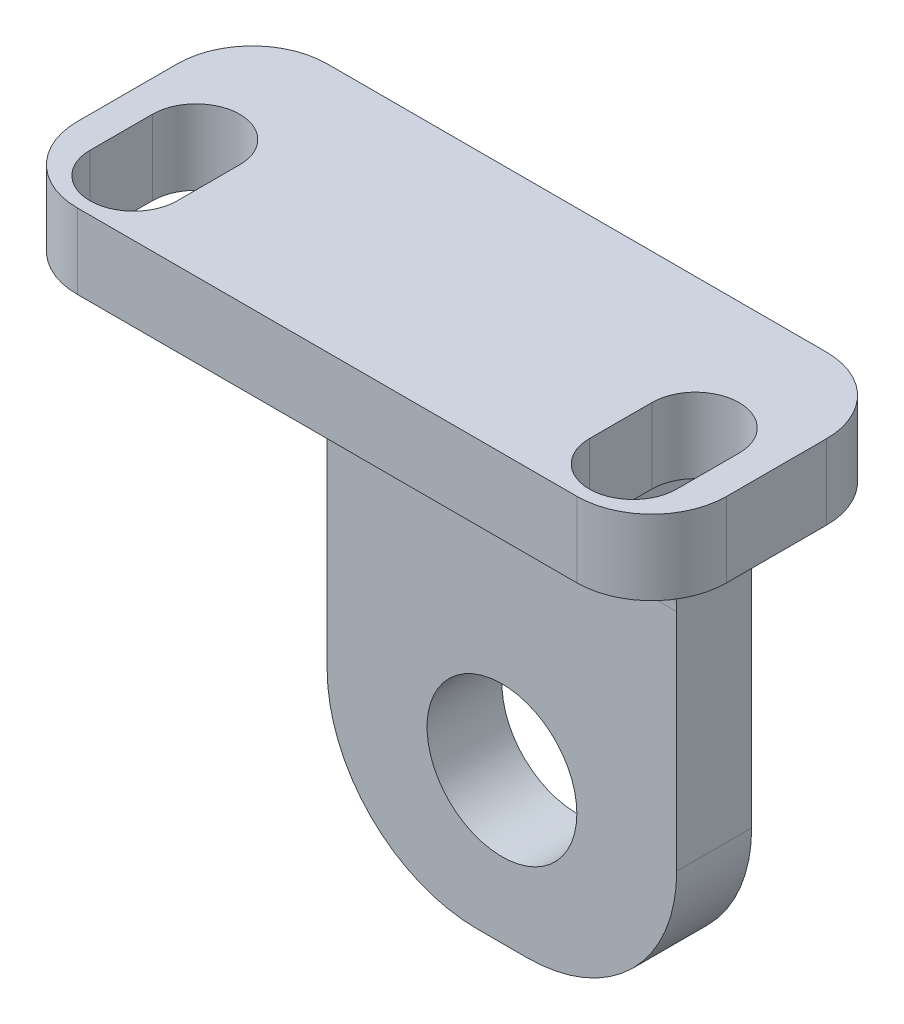
SolidWorks part; units mm, degrees
ref_plane "Front Plane" through (0, 0, 0) normal (0, 0, 1) x (1, 0, 0)
ref_plane "Top Plane" through (0, 0, 0) normal (0, 1, 0) x (1, 0, 0)
ref_plane "Right Plane" through (0, 0, 0) normal (1, 0, 0) x (0, 0, -1)
sketch "Sketch1" plane through (0, 0, 0) normal (0, 1, 0) x (1, 0, 0)
  line L1 (-7, 0) -> (7, 0)
  line L2 (-7, 0) -> (-7, -3)
  line L3 (-7, -3) -> (7, -3)
  line L4 (7, 0) -> (7, -3)
  line L5 (-7, 0) -> (7, -3) construction
  line L6 (-7, -3) -> (7, 0) construction
  point P0 (0, -1.5)
  dimension "D1" = 3
  dimension "D2" = 14
extrude "Boss-Extrude1" add sketch "Sketch1" along normal blind 24
sketch "Sketch2" plane through (0, 0, 3) normal (0, 0, 1) x (1, 0, 0)
  line L1 (-7, 0) -> (7, 0) construction
  circle A0 centre (0, 6) radius 3
  dimension "D1" = 6
  dimension "D2" = 6
extrude "Cut-Extrude1" cut sketch "Sketch2" against normal up to next
sketch "Sketch3" plane through (0, 0, 0) normal (0, 0, 1) x (1, 0, 0)
  line L1 (13, 21) -> (-13, 21)
  line L2 (13, 21) -> (13, 24)
  line L3 (13, 24) -> (-13, 24)
  line L4 (-13, 21) -> (-13, 24)
  line L5 (-7, 24) -> (7, 24) construction
  line L6 (-7, 24) -> (-7, 0) construction
  line L7 (7, 24) -> (7, 0) construction
  dimension "D1" = 6
  dimension "D2" = 6
  dimension "D3" = 3
extrude "Boss-Extrude2" add sketch "Sketch3" along normal blind 10
sketch "Sketch4" plane through (0, 24, 0) normal (0, 1, 0) x (1, 0, 0)
  line L0 (-10, -7.75) -> (-10, -5.25) construction
  line L1 (-11.75, -7.75) -> (-11.75, -5.25)
  line L2 (-8.25, -7.75) -> (-8.25, -5.25)
  line L3 (0, -5.5) -> (0, 5.5) construction
  line L4 (10, -7.75) -> (10, -5.25) construction
  line L5 (11.75, -7.75) -> (11.75, -5.25)
  line L6 (8.25, -7.75) -> (8.25, -5.25)
  line L7 (13, 0) -> (-13, 0) construction
  arc A0 (-11.75, -7.75) -> (-8.25, -7.75) centre (-10, -7.75) ccw
  arc A1 (-8.25, -5.25) -> (-11.75, -5.25) centre (-10, -5.25) ccw
  arc A2 (11.75, -7.75) -> (8.25, -7.75) centre (10, -7.75) cw
  arc A3 (8.25, -5.25) -> (11.75, -5.25) centre (10, -5.25) cw
  point P2 (-10, -6.5)
  point P11 (10, -6.5)
  point P18 (0, 0)
  point P19 (0, 0)
  dimension "D1" = 2.5
  dimension "D2" = 3.5
  dimension "D3" = 6.5
  dimension "D4" = 10
extrude "Cut-Extrude2" cut sketch "Sketch4" against normal up to next contours A3 L6 A2 L5 | L2 A1 L1 A0
fillet "Fillet1" radius 3 4 edges at (13, 22.5, 0) (13, 22.5, 10) (-13, 22.5, 0) (-13, 22.5, 10)
fillet "Fillet2" radius 6 3 edges at (-7, 0, 1.5) (7, 0, 1.5) (0, 21, 3)
equation "\"D2@Sketch3\"=\"D1@Sketch3\""
